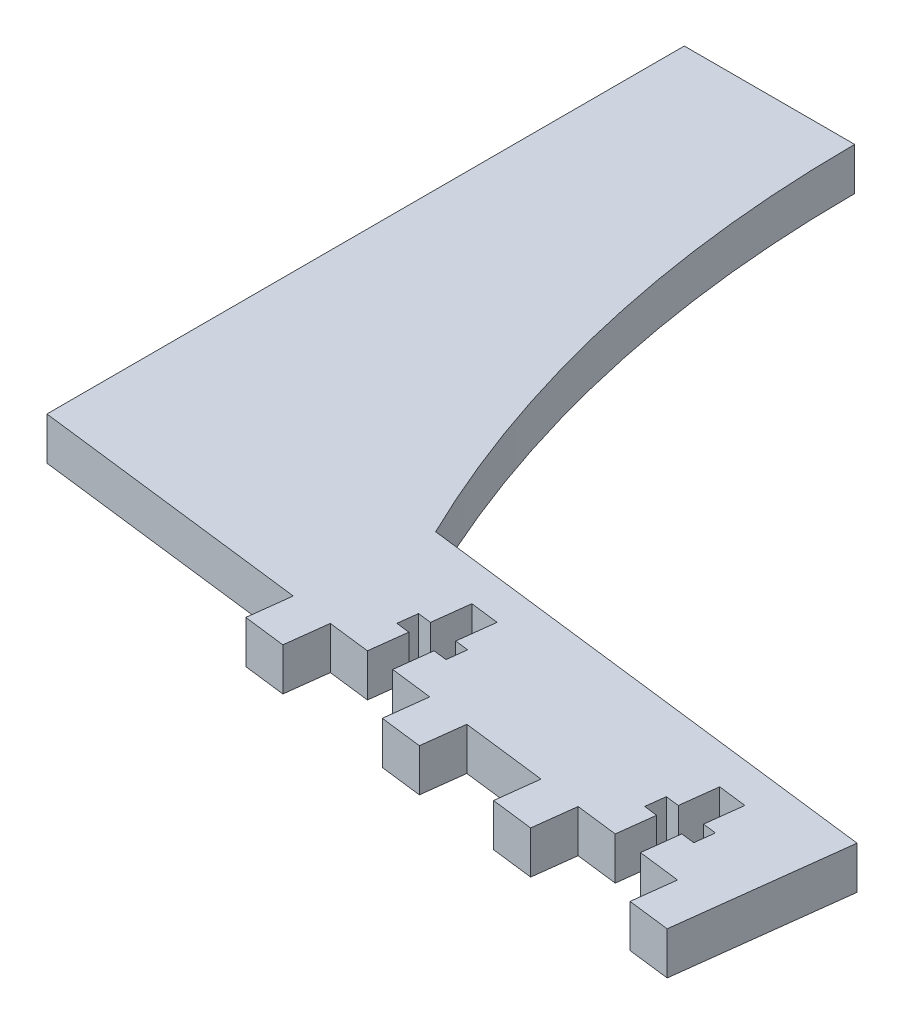
SolidWorks part; units mm, degrees
ref_plane "Front Plane" through (0, 0, 0) normal (0, 0, 1) x (1, 0, 0)
ref_plane "Top Plane" through (0, 0, 0) normal (0, 1, 0) x (1, 0, 0)
ref_plane "Right Plane" through (0, 0, 0) normal (1, 0, 0) x (0, 0, -1)
sketch "Sketch1" plane through (0, 0, 0) normal (0, 1, 0) x (1, 0, 0)
  line L0 (83.9515, -10.308) -> (71.3462, -8.7602)
  line L1 (113.448, -13.9297) -> (113.448, 81.0663) construction
  line L2 (113.448, 81.0663) -> (0, 94.996) construction
  line L3 (0, 94.996) -> (0, 0)
  line L4 (0, 94.996) -> (47.5611, 94.996) construction
  line L5 (0, 0) -> (41.8497, -5.1385)
  line L6 (0, 94.996) -> (25.4, 94.996)
  line L7 (25.4, 94.996) -> (25.4, 65.4131) construction
  line L8 (113.448, -13.9297) -> (115.7696, 4.9783)
  line L9 (115.7696, 4.9783) -> (44.1713, 13.7695)
  line L10 (41.8497, -5.1385) -> (45.7915, 26.9645) construction
  arc A0 (25.4, 94.996) -> (44.1713, 13.7695) centre (210.5256, 94.996) ccw
  line B0 (90.2542, -11.0818) -> (89.4803, -17.3845)
  line B1 (89.4803, -17.3845) -> (83.1777, -16.6106)
  line B2 (83.1777, -16.6106) -> (83.9515, -10.308)
  line B3 (96.5569, -11.8557) -> (97.2314, -6.362)
  line B4 (97.2314, -6.362) -> (95.2056, -6.1132)
  line B5 (95.2056, -6.1132) -> (95.5591, -3.2348)
  line B6 (95.5591, -3.2348) -> (97.5848, -3.4836)
  line B7 (97.5848, -3.4836) -> (98.2594, 2.0102)
  line B8 (98.2594, 2.0102) -> (102.5452, 1.4839)
  line B9 (102.5452, 1.4839) -> (101.8707, -4.0098)
  line B10 (101.8707, -4.0098) -> (103.8964, -4.2585)
  line B11 (103.8964, -4.2585) -> (103.543, -7.1369)
  line B12 (103.543, -7.1369) -> (101.5172, -6.8882)
  line B13 (101.5172, -6.8882) -> (100.8427, -12.3819)
  line B14 (100.4023, 1.7471) -> (98.6998, -12.1188) construction
  line B15 (107.1454, -13.1558) -> (100.8427, -12.3819)
  line B16 (112.6742, -20.2323) -> (113.448, -13.9297)
  line B17 (90.2542, -11.0818) -> (96.5569, -11.8557)
  line B18 (106.3715, -19.4585) -> (112.6742, -20.2323)
  line B19 (107.1454, -13.1558) -> (106.3715, -19.4585)
  line B20 (48.1524, -5.9124) -> (47.3785, -12.215)
  line B21 (47.3785, -12.215) -> (41.0758, -11.4412)
  line B22 (41.0758, -11.4412) -> (41.8497, -5.1385)
  line B23 (54.4551, -6.6862) -> (55.1296, -1.1925)
  line B24 (55.1296, -1.1925) -> (53.1038, -0.9438)
  line B25 (53.1038, -0.9438) -> (53.4572, 1.9346)
  line B26 (53.4572, 1.9346) -> (55.483, 1.6859)
  line B27 (55.483, 1.6859) -> (56.1576, 7.1796)
  line B28 (56.1576, 7.1796) -> (60.4434, 6.6534)
  line B29 (60.4434, 6.6534) -> (59.7688, 1.1597)
  line B30 (59.7688, 1.1597) -> (61.7946, 0.9109)
  line B31 (61.7946, 0.9109) -> (61.4412, -1.9675)
  line B32 (61.4412, -1.9675) -> (59.4154, -1.7187)
  line B33 (59.4154, -1.7187) -> (58.7409, -7.2125)
  line B34 (58.3005, 6.9165) -> (56.598, -6.9494) construction
  line B35 (65.0435, -7.9863) -> (58.7409, -7.2125)
  line B36 (70.5723, -15.0629) -> (71.3462, -8.7602)
  line B37 (48.1524, -5.9124) -> (54.4551, -6.6862)
  line B38 (64.2697, -14.289) -> (70.5723, -15.0629)
  line B39 (65.0435, -7.9863) -> (64.2697, -14.289)
  dimension "D1" = 7
  dimension "D2" = 97
  dimension "D3" = 94.996
  dimension "D4" = 114.3
  dimension "D5" = 12.7
  dimension "D6" = 5.08
  dimension "D7" = 25.4
sketch_block_instance "Male T-slot assembly-1"
sketch_block "Male T-slot assembly" parameters "D1"=6.35, "D2"=6.35, "D3"=4.318, "D4"=2.9, "D5"=8.4, "D6"=13.97, "D7"=6.35
sketch_block_instance "Male T-slot assembly-2"
extrude "Boss-Extrude1" add sketch "Sketch1" along normal blind 6.35
